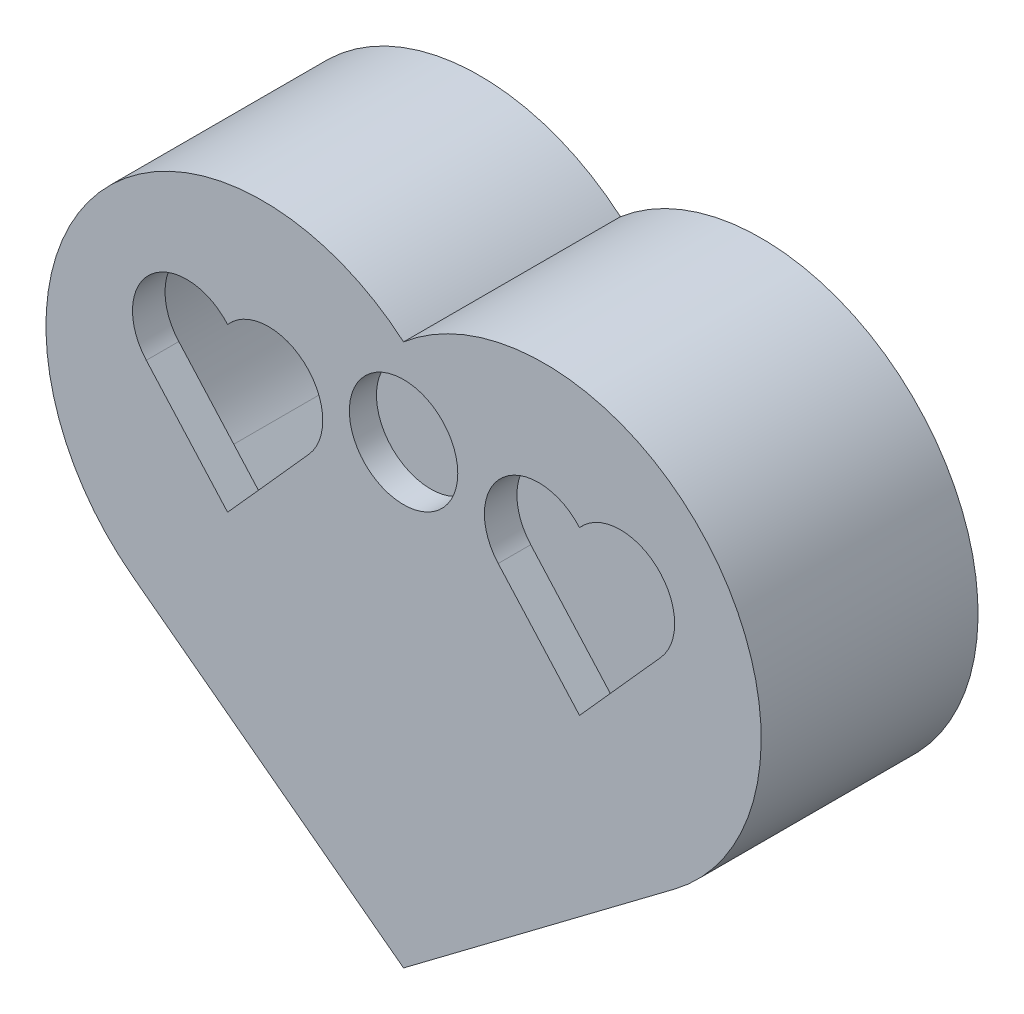
SolidWorks part; units mm, degrees
ref_plane "前基準面" through (0, 0, 0) normal (0, 0, 1) x (1, 0, 0)
ref_plane "上基準面" through (0, 0, 0) normal (0, 1, 0) x (1, 0, 0)
ref_plane "右基準面" through (0, 0, 0) normal (1, 0, 0) x (0, 0, -1)
sketch "草圖1" plane through (0, 0, 0) normal (0, 0, 1) x (1, 0, 0)
  line L0 (-24.197, 36.9236) -> (0.803, 18.1243)
  line L1 (0.803, 18.1243) -> (25.803, 36.9236)
  line L2 (0.803, 68.1243) -> (0.803, 18.1243) construction
  line L3 (-24.197, 36.9236) -> (25.803, 36.9236) construction
  line L4 (-12.1769, 52.9084) -> (13.7829, 52.9084) construction
  arc A0 (25.803, 36.9236) -> (0.803, 68.1243) centre (13.7829, 52.9084) ccw
  arc A1 (-24.197, 36.9236) -> (0.803, 68.1243) centre (-12.1769, 52.9084) cw
  dimension "D1" = 50
  dimension "D3" = 20
  dimension "D4" = 20
  dimension "D2" = 50
extrude "填料-伸長1" add sketch "草圖1" along normal mid plane 20
sketch "草圖2" plane through (0, 0, 10) normal (0, 0, 1) x (1, 0, 0)
  line L0 (0.803, 68.1243) -> (0.803, 60.1243) construction
  circle A0 centre (0.803, 60.1243) radius 5
  dimension "D1" = 10
  dimension "D2" = 8
extrude "除料-伸長1" cut sketch "草圖2" against normal blind 2.5
sketch "草圖3" plane through (0, 0, 0) normal (0, 0, 1) x (1, 0, 0)
  line L0 (0.803, 20.1243) -> (23.303, 45.2823)
  line L1 (-21.697, 45.2823) -> (0.803, 20.1243)
  arc A0 (23.303, 45.2823) -> (0.803, 65.1243) centre (12.1222, 55.2818) ccw
  arc A1 (0.803, 65.1243) -> (-21.697, 45.2823) centre (-10.5162, 55.2818) ccw
  dimension "D1" = 15
  dimension "D2" = 15
  dimension "D3" = 45
  dimension "D4" = 45
  dimension "D5" = 2
extrude "除料-伸長2" cut sketch "草圖3" against normal mid plane 14
sketch "草圖4" plane through (0, 0, -10) normal (0, 0, -1) x (-1, 0, 0)
  line L0 (7.9239, 54.7911) -> (15.4239, 46.4052)
  line L1 (15.4239, 46.4052) -> (22.9239, 54.7911)
  line L2 (-17.0299, 46.4052) -> (-24.5299, 54.7911)
  line L3 (-17.0299, 46.4052) -> (-9.5299, 54.7911)
  line L4 (-20.803, 58.1243) -> (19.197, 58.1243) construction
  line L5 (-0.803, 18.1243) -> (-0.803, 75.59) construction
  arc A0 (7.9239, 54.7911) -> (15.4239, 61.4052) centre (11.6509, 58.1243) cw
  arc A1 (22.9239, 54.7911) -> (15.4239, 61.4052) centre (19.197, 58.1243) ccw
  arc A2 (-24.5299, 54.7911) -> (-17.0299, 61.4052) centre (-20.803, 58.1243) cw
  arc A3 (-9.5299, 54.7911) -> (-17.0299, 61.4052) centre (-13.2568, 58.1243) ccw
  point P12 (-0.803, 58.1243)
  dimension "D1" = 5
  dimension "D2" = 5
  dimension "D5" = 5
  dimension "D6" = 5
  dimension "D3" = 15
  dimension "D4" = 15
  dimension "D7" = 15
  dimension "D9" = 40
  dimension "D10" = 40
extrude "除料-伸長3" cut sketch "草圖4" against normal blind 20
